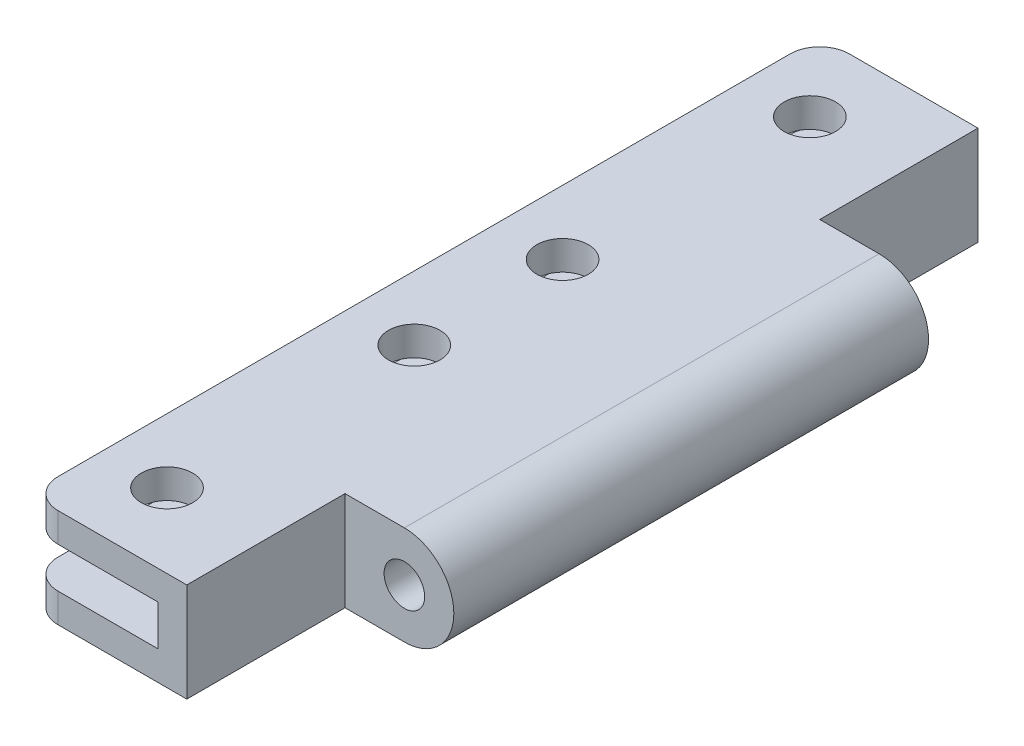
SolidWorks part; units mm, degrees
ref_plane "前视基准面" through (0, 0, 0) normal (0, 0, 1) x (1, 0, 0)
ref_plane "上视基准面" through (0, 0, 0) normal (0, 1, 0) x (1, 0, 0)
ref_plane "右视基准面" through (0, 0, 0) normal (1, 0, 0) x (0, 0, -1)
sketch "草图1" plane through (0, 0, 0) normal (0, 0, 1) x (1, 0, 0)
  line L0 (-228.2325, 0) -> (11183.3925, 0) construction
  line L1 (0, -228.2325) -> (0, 11183.3925) construction
  line L2 (0, 5) -> (22, 5)
  line L3 (22, -5) -> (0, -5)
  line L4 (0, -5) -> (0, 5)
  line L5 (22, -1005) -> (22, 48995) construction
  arc A0 (22, 5) -> (22, -5) centre (22, 0) cw
  circle A2 centre (22, 0) radius 2.05
  dimension "D1" = 4.1
  dimension "D2" = 5
  dimension "D4" = 5
  dimension "D3" = 0
  dimension "D5" = 22
extrude "凸台-拉伸1" add sketch "草图1" along normal blind 80
sketch "草图2" plane through (0, 0, 80) normal (0, 0, 1) x (1, 0, 0)
  line L0 (0, 2.05) -> (13.1, 2.05)
  line L1 (0, 5) -> (0, -5) construction
  line L2 (13.1, 2.05) -> (13.1, -2.05)
  line L3 (13.1, -2.05) -> (0, -2.05)
  line L4 (0, -2.05) -> (0, 2.05)
  line L5 (-1000, 0) -> (49000, 0) construction
  dimension "D1" = 4.1
  dimension "D2" = 13.1
extrude "切除-拉伸1" cut sketch "草图2" against normal blind 95
sketch "草图4" plane through (0, 5, 0) normal (0, 1, 0) x (1, 0, 0)
  line L0 (0, -80) -> (0, 0) construction
  line L1 (22, -80) -> (22, 0) construction
  line L2 (-985, -40) -> (49015, -40) construction
  circle A2 centre (6.5, -32.5) radius 2.6
  circle A3 centre (6.5, -7.5) radius 2.6
  circle A4 centre (6.5, -72.5) radius 2.6
  circle A5 centre (6.5, -47.5) radius 2.6
  point P11 (22, -40)
  dimension "D2" = 6.5
  dimension "D3" = 5.2
  dimension "D1" = 7.5
  dimension "D5" = 25
extrude "切除-拉伸2" cut sketch "草图4" against normal blind 20
sketch "草图5" plane through (0, 5, 0) normal (0, 1, 0) x (1, 0, 0)
  line L0 (-989.0255, -40) -> (49010.9745, -40) construction
  line L1 (22, -80) -> (22, 0) construction
  line L2 (22, -1016) -> (22, 48984) construction
  line L7 (22, 984) -> (22, -49016) construction
  line L12 (22, 0) -> (32.4965, 0)
  line L13 (32.4965, 0) -> (32.4965, -16)
  line L16 (22, 0) -> (16, 0)
  line L17 (16, 0) -> (16, -16)
  line L21 (16, -16) -> (32.4965, -16)
  line L22 (22, 0) -> (0, 0) construction
  line L23 (16, -64) -> (32.4965, -64)
  line L24 (16, -80) -> (16, -64)
  line L25 (22, -80) -> (16, -80)
  line L26 (32.4965, -80) -> (32.4965, -64)
  line L27 (22, -80) -> (32.4965, -80)
  point P5 (22, -40)
  point P16 (25.761, -40)
  point P17 (22, -40)
  point P19 (13.261, -40)
  dimension "D1" = 16
  dimension "D2" = 6
ref_plane "基准面4" through (13.1, 2.05, 0) normal (0, 0, 1) x (1, 0, 0)
extrude "切除-拉伸5" cut sketch "草图5" against normal blind 20
ref_plane "基准面5" through (22, -5, 64) normal (0, 0, -1) x (-1, 0, 0)
fillet "圆角1" radius 3 4 edges at (0, -3.525, 0) (0, 3.525, 0) (0, 3.525, 80) (0, -3.525, 80)
